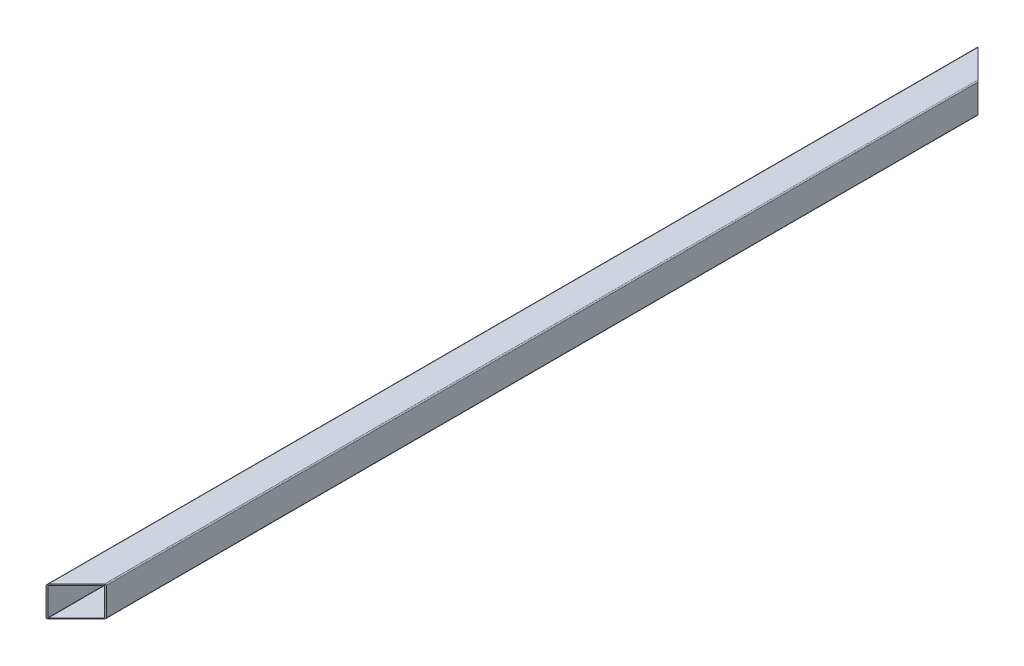
SolidWorks part; units mm, degrees
material "AISI 1020 Steel, Cold Rolled"
ref_plane "Front Plane" through (0, 0, 0) normal (0, 0, 1) x (1, 0, 0)
ref_plane "Top Plane" through (0, 0, 0) normal (0, 1, 0) x (1, 0, 0)
ref_plane "Right Plane" through (0, 0, 0) normal (1, 0, 0) x (0, 0, -1)
sketch "Sketch1" plane through (0, 0, 0) normal (0, 1, 0) x (1, 0, 0)
  line L0 (0, 0) -> (0, 1236)
  dimension "D1" = 1236
other "Structural Member1"
ref_plane "Plane1" through (0, 0, 0) normal (0, 0, -1) x (-1, 0, 0)
sketch "Sketch12" plane through (0, 0, 0) normal (0, 0, -1) x (-1, 0, 0)
  line L0 (-18.5, -18.8) -> (18.5, -18.8)
  line L1 (-18.8, -18.5) -> (-18.8, 18.5)
  line L2 (18.5, 18.8) -> (-18.5, 18.8)
  line L3 (18.8, 18.5) -> (18.8, -18.5)
  line L4 (-18.5, -20) -> (18.5, -20)
  line L5 (-20, -18.5) -> (-20, 18.5)
  line L6 (18.5, 20) -> (-18.5, 20)
  line L7 (20, 18.5) -> (20, -18.5)
  arc A0 (20, 18.5) -> (18.5, 20) centre (18.5, 18.5) ccw
  arc A1 (18.5, -20) -> (20, -18.5) centre (18.5, -18.5) ccw
  arc A2 (-20, -18.5) -> (-18.5, -20) centre (-18.5, -18.5) ccw
  arc A3 (-18.5, 20) -> (-20, 18.5) centre (-18.5, 18.5) ccw
  arc A4 (-18.5, 18.8) -> (-18.8, 18.5) centre (-18.5, 18.5) ccw
  arc A5 (18.8, 18.5) -> (18.5, 18.8) centre (18.5, 18.5) ccw
  arc A6 (18.5, -18.8) -> (18.8, -18.5) centre (18.5, -18.5) ccw
  arc A7 (-18.8, -18.5) -> (-18.5, -18.8) centre (-18.5, -18.5) ccw
  point P0 (-20, 0)
  point P1 (20, 0)
  point P2 (0, 20)
  point P3 (0, -20)
  point P4 (0, 0)
  point P5 (-20, -20)
  point P6 (20, -20)
  point P7 (20, 20)
  point P8 (-20, 20)
  point P33 (0, 0)
  dimension "D1" = 1.5
  dimension "Thickness" = 1.2
  dimension "V_leg" = 40
sketch "Sketch13" plane through (0, 20, 0) normal (0, 1, 0) x (1, 0, 0)
  line L0 (-20, 1236) -> (33.292, 1182.708)
  line L1 (33.292, 1182.708) -> (17.4146, 1269.8648)
  line L2 (17.4146, 1269.8648) -> (-20, 1236)
  line L3 (-18.5, 1236) -> (18.5, 1236) construction
  line L4 (-18.5, 618) -> (18.5, 618) construction
  line L5 (-18.5, 1236) -> (-18.5, 0) construction
  line L6 (18.5, 1236) -> (18.5, 0) construction
  line L7 (17.4146, -33.8648) -> (-20, 0)
  line L8 (33.292, 53.292) -> (17.4146, -33.8648)
  line L9 (-20, 0) -> (33.292, 53.292)
  dimension "D1" = 45
extrude "Cut-Extrude1" cut sketch "Sketch13" against normal blind 50
